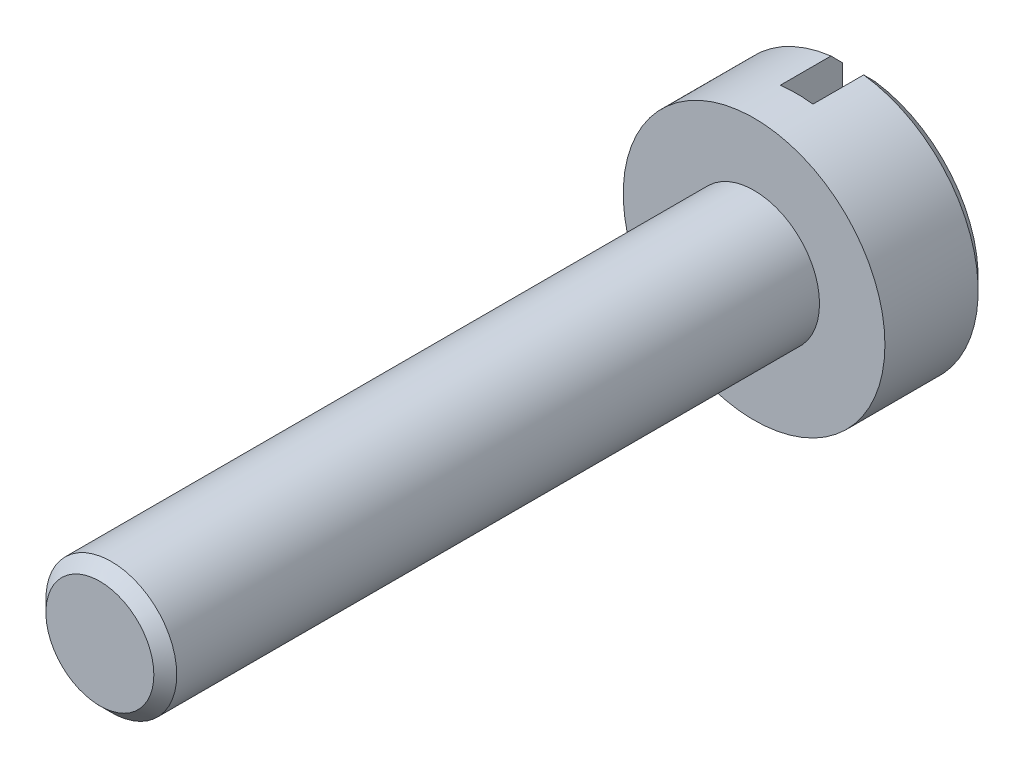
SolidWorks part; units mm, degrees
ref_plane "Спереди" through (0, 0, 0) normal (0, 0, 1) x (1, 0, 0)
ref_plane "Сверху" through (0, 0, 0) normal (0, 1, 0) x (1, 0, 0)
ref_plane "Справа" through (0, 0, 0) normal (1, 0, 0) x (0, 0, -1)
sketch "Эскиз1" plane through (0, 0, 0) normal (0, 0, 1) x (1, 0, 0)
  circle A0 centre (0, 0) radius 4
  dimension "D1" = 8
extrude "Вытянуть1" add sketch "Эскиз1" along normal blind 3.2
sketch "Эскиз2" plane through (0, 0, 3.2) normal (0, 0, 1) x (1, 0, 0)
  circle A0 centre (0, 0.086) radius 2
  dimension "D1" = 4
extrude "Вытянуть2" add sketch "Эскиз2" along normal blind 20
sketch "Эскиз3" plane through (0, 0, 0) normal (0, 0, -1) x (-1, 0, 0)
  line L0 (0, 4.2033) -> (0, -4.4901) construction
  line L1 (0.5, 4.2033) -> (0.5, -4.4901)
  line L2 (-0.5, 4.5703) -> (-0.5, -4.708)
  line L3 (-0.5, 4.5703) -> (0.5, 4.2033)
  line L4 (-0.5, -4.708) -> (0.5, -4.4901)
  dimension "D1" = 1
  dimension "D2" = 0.5
extrude "Вырез-Вытянуть1" cut sketch "Эскиз3" against normal blind 1.9
chamfer "Фаска1" distance 0.35 angle 45
